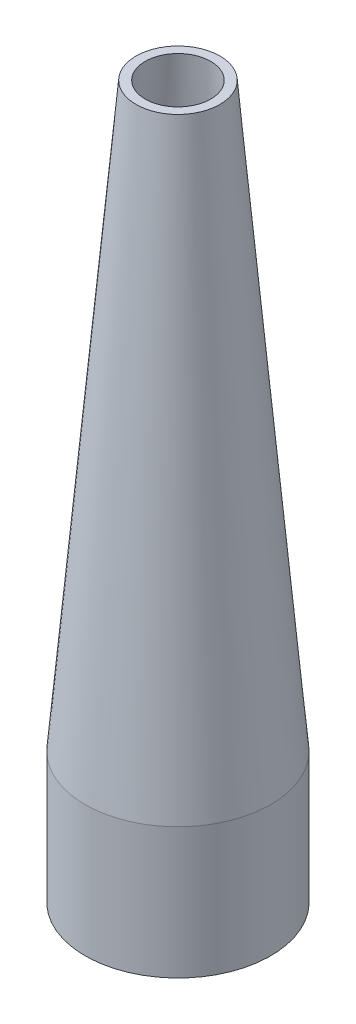
SolidWorks part; units mm, degrees
material "S-Glass Fiber"
ref_plane "Front Plane" through (0, 0, 0) normal (0, 0, 1) x (1, 0, 0)
ref_plane "Top Plane" through (0, 0, 0) normal (0, 1, 0) x (1, 0, 0)
ref_plane "Right Plane" through (0, 0, 0) normal (1, 0, 0) x (0, 0, -1)
sketch "Sketch1" plane through (0, 0, 0) normal (0, 0, 1) x (1, 0, 0)
  line L0 (0, 0) -> (0, 49.1635) construction
  line L1 (9.525, 49.1635) -> (12.2022, 49.1635)
  line L2 (12.2022, 49.1635) -> (26.9875, -119.8334)
  line L3 (26.9875, -119.8334) -> (24.3103, -119.8334)
  line L4 (24.3103, -119.8334) -> (9.525, 49.1635)
  line L6 (24.3103, -119.8334) -> (26.9875, -119.8334)
  line L7 (24.3103, -119.8334) -> (24.3103, -157.9334)
  line L8 (24.3103, -157.9334) -> (26.9875, -157.9334)
  line L9 (26.9875, -119.8334) -> (26.9875, -157.9334)
  line L10 (26.9875, -157.9334) -> (26.9875, -907.2334) construction
  point P11 (26.9875, -157.9334)
  point P15 (24.3103, -157.9334)
revolve "Revolve1" add sketch "Sketch1" angle 360 about L0
